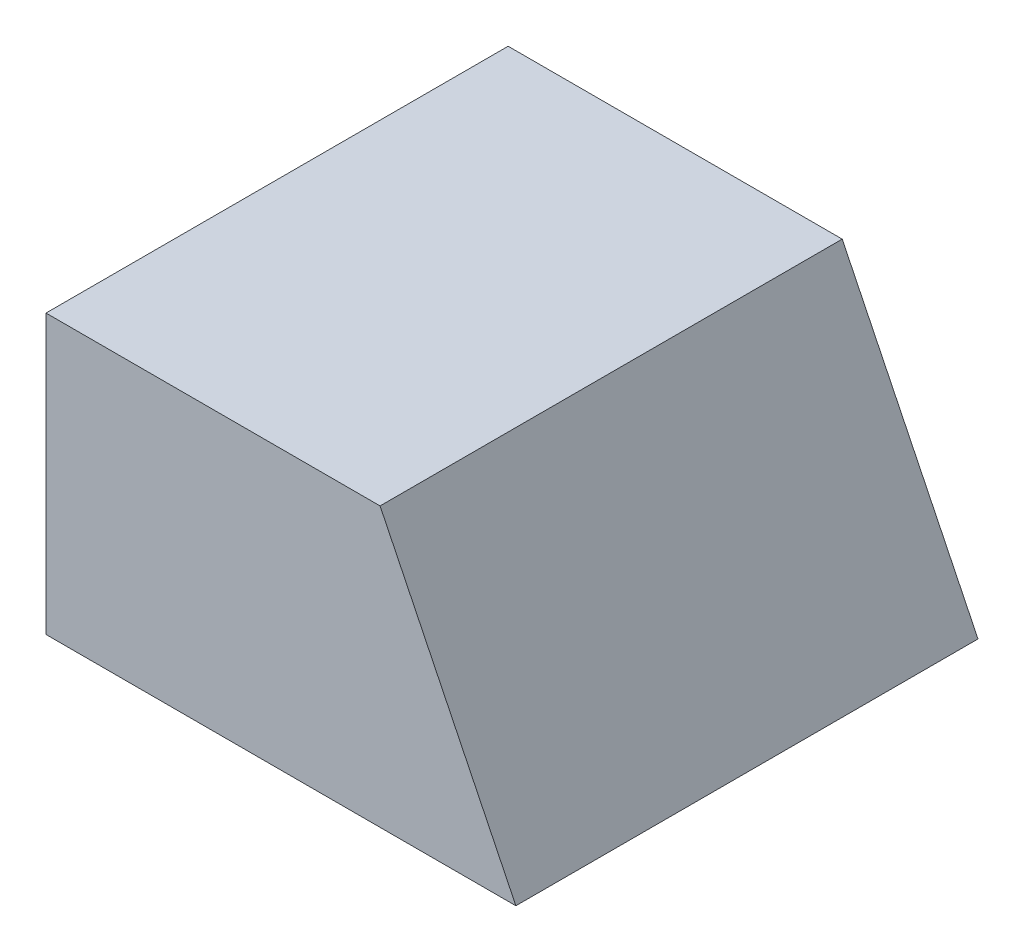
SolidWorks part; units mm, degrees
material "AISI 1020"
ref_plane "Спереди" through (0, 0, 0) normal (0, 0, 1) x (1, 0, 0)
ref_plane "Сверху" through (0, 0, 0) normal (0, 1, 0) x (1, 0, 0)
ref_plane "Справа" through (0, 0, 0) normal (1, 0, 0) x (0, 0, -1)
sketch "Эскиз1" plane through (0, 0, 0) normal (0, 0, 1) x (1, 0, 0)
  line L0 (0, 0) -> (4219.457, 0) construction
  line L1 (4219.457, 0) -> (3000, 2500) construction
  line L2 (0, 2500) -> (3000, 2500) construction
  line L3 (0, 0) -> (4219.457, 0)
  line L4 (4219.457, 0) -> (3000, 2500)
  line L5 (0, 2500) -> (3000, 2500)
  line L6 (0, 2500) -> (0, 0)
extrude "Бобышка-Вытянуть2" add sketch "Эскиз1" against normal up to surface (4150 mm away)
